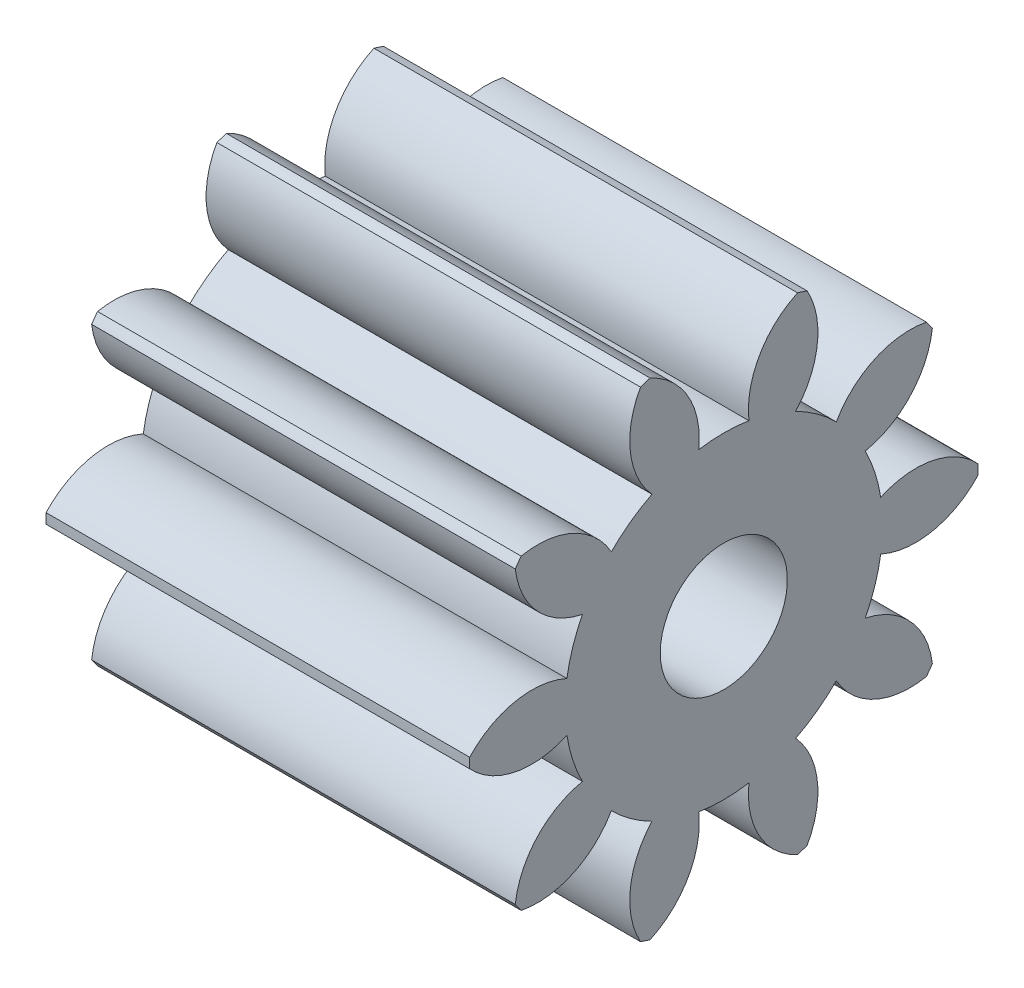
SolidWorks part; units mm, degrees
ref_plane "Plane1" through (0, 0, 0) normal (0, 0, 1) x (1, 0, 0)
ref_plane "Plane2" through (0, 0, 0) normal (0, 1, 0) x (1, 0, 0)
ref_plane "Plane3" through (0, 0, 0) normal (1, 0, 0) x (0, 0, -1)
other "Configuration Table"
sketch "HoldingSke" plane through (0, 0, 0) normal (0, 1, 0) x (1, 0, 0)
  line L0 (0, 0) -> (0.9848, -0.1736)
  line L1 (-15, 0) -> (100, 0) construction
  line L2 (0, 0) -> (-2.1039, 2.3779)
  line L3 (0, 0) -> (-11.863, 4.5341)
  line L4 (0, 0) -> (8.5048, 1.4996)
  line L5 (0, 0) -> (-46.8476, -17.4728)
  line L6 (0, 0) -> (-8.2896, -5.593)
  line L7 (-2.1039, 2.3779) -> (8.6586, 51.2059)
  line L8 (-76.2, 54.61) -> (-75.7, 54.61)
  line L9 (-71.009, 38.7566) -> (-53.1078, 45.2721)
  line L10 (-76.2, 71.12) -> (104.1128, 71.12)
  line L11 (0, 0) -> (-10, 0)
  line L12 (-76.2, 101.6) -> (-76.162, 101.6)
  line L13 (24.9733, 27.94) -> (52.9518, 28.4284)
  line L14 (24.9733, 27.94) -> (24.9743, 27.94)
  line L15 (24.9733, 27.94) -> (100.4006, 29.5858)
  line L16 (-63.627, -1) -> (-12.827, -1)
  circle A0 centre (0, 0) radius 1.5
  circle A1 centre (0, 0) radius 3.749
  circle A2 centre (0, 0) radius 37.5
  circle A3 centre (0, 0) radius 1.5
  dimension "MHD" = 7.498
  dimension "Hub_dia" = 75
  dimension "Bore" = 3
  dimension "MBD" = 3
  dimension "Num_teeth" = 10
  dimension "Pitch" = 1
  dimension "Overall_len" = 50
  dimension "Show_teeth" = 10
  dimension "Thickness" = 10
  dimension "OAL" = 50.0001
  dimension "T_dim" = 0.5
  dimension "Ap" = 20
  dimension "H" = 19.05
  dimension "Pitch_radius" = 180.3128
  dimension "Width" = 10
  dimension "Backlash" = 0.038
  dimension "Addendum_fac" = 1
  dimension "Dedendum_fac" = 1.25
  dimension "Clearance_fac" = 0.25
  dimension "Dedendum_add" = 0.001
  dimension "Module" = 1
sketch "BasProSke" plane through (0, 0, 0) normal (0, 1, 0) x (1, 0, 0)
  line L0 (-10, 0) -> (60, 0) construction
  line L1 (0, 0) -> (0, 6)
  line L2 (0, 0) -> (10, 0)
  line L3 (10, 0) -> (10, 6)
  line L4 (10, 6) -> (0, 6)
  dimension "Thickness" = 10
  dimension "Diameter" = 12
revolve "Base-Revolve" add sketch "BasProSke" angle 360 about L0
sketch "TooCutSke" plane through (0, 0, 0) normal (1, 0, 0) x (0, 0, -1)
  line L1 (0, 0) -> (0, 107) construction
  line L2 (0, 0) -> (-0.8485, 4.9275) construction
  line L3 (0, 0) -> (-3.0584, 9.4126) construction
  line L4 (-0.8485, 4.9275) -> (-1.5292, 4.7063) construction
  arc A0 (0.5928, 3.7018) -> (-0.5928, 3.7018) centre (0, 0) ccw
  arc A1 (1.7758, 5.7578) -> (-1.7758, 5.7578) centre (0, 0) ccw
  circle A2 centre (0, 0) radius 5 construction
  circle A3 centre (0, 0) radius 4.6985 construction
  arc A4 (-0.5928, 3.7018) -> (-1.7758, 5.7578) centre (-2.5801, 3.9267) ccw
  arc A5 (1.7758, 5.7578) -> (0.5928, 3.7018) centre (2.5801, 3.9267) ccw
  dimension "Root_dia" = 7.498
  dimension "Overcut_dia" = 12.0508
  dimension "Pitch_dia" = 10
  dimension "Base_dia" = 9.3969
  dimension "Flank_rad" = 2
  dimension "Half_ang" = 18
  dimension "Half_CT" = 0.7157
extrude "ToothCut" cut sketch "TooCutSke" along normal through all
fillet "Breaks" [suppressed] radius 0.02
fillet "RootFillets" [suppressed] radius 0.251
pattern_circular "TeethCuts" count 10 every 36 about axis through (-10, 0, 0) along (1, 0, 0) of "ToothCut", "RootFillets", "Breaks"
sketch "HubNeaOneSke" plane through (0, 0, 0) normal (-1, 0, 0) x (0, 0, 1)
  circle A0 centre (0, 0) radius 3.749
  dimension "Diameter" = 7.498
extrude "HubNearOne" [suppressed] add sketch "HubNeaOneSke" along normal blind 40.0001
sketch "HubNeaBotSke" plane through (0, 0, 0) normal (-1, 0, 0) x (0, 0, 1)
  circle A0 centre (0, 0) radius 3.749
  dimension "Diameter" = 7.498
extrude "HubNearBoth" [suppressed] add sketch "HubNeaBotSke" along normal blind 20
ref_plane "FarPln" through (10, 0, 0) normal (1, 0, 0) x (0, 0, -1)
sketch "HubFarSke" plane through (10, 0, 0) normal (1, 0, 0) x (0, 0, -1)
  circle A0 centre (0, 0) radius 3.749
  dimension "Diameter" = 7.498
extrude "HubFar" [suppressed] add sketch "HubFarSke" along normal blind 20
sketch "BorSke" plane through (0, 0, 0) normal (1, 0, 0) x (0, 0, -1)
  circle A0 centre (0, 0) radius 1.5
  dimension "Diameter" = 3
extrude "Bore" cut sketch "BorSke" along normal mid plane 100.0001
sketch "KeySke" plane through (0, 0, 0) normal (1, 0, 0) x (0, 0, -1)
  line L0 (-0.6, 0) -> (-0.6, 2)
  line L1 (-0.6, 2) -> (0.6, 2)
  line L2 (0.6, 2) -> (0.6, 0)
  line L3 (0, 0) -> (0, 34) construction
  line L4 (-0.6, 0) -> (0.6, 0)
  dimension "Offset" = 2
  dimension "Width" = 1.2
extrude "Keyway" [suppressed] cut sketch "KeySke" along normal mid plane 100.0001
pattern_circular "Keyway2" [suppressed] count 2 every 90 about axis through (-10, 0, 0) along (1, 0, 0)
equation "' \"Module@HoldingSke\" = 6.35"
equation "' \"Num_teeth@HoldingSke\" = 12"
equation "' \"Ap@HoldingSke\" =  20"
equation "' \"Ap@HoldingSke\" = 20"
equation "' \"Width@HoldingSke\" = 0.5 * 25.4"
equation "' \"Hub_dia@HoldingSke\"= 1 * 25.4"
equation "' \"Hub_dia@HoldingSke\" = 1 * 25.4"
equation "' \"Overall_len@HoldingSke\" = 1.0 * 25.4"
equation "' \"Bore@HoldingSke\" = 0.75 * 25.4"
equation "' \"T_dim@HoldingSke\" = 0.1 * 25.4"
equation "' \"Width@KeySke\" = 0.25 * 25.4"
equation "' \"Show_teeth@HoldingSke\" = 13"
equation "' \"Backlash@HoldingSke\" = 0.009 * 25.4"
equation "' \"Addendum_fac@HoldingSke\" = 1.0"
equation "' \"Dedendum_fac@HoldingSke\" = 1.25"
equation "' \"Dedendum_add@HoldingSke\" = 0.00005 * 25.4"
equation "' \"Clearance_fac@HoldingSke\" = 0.25"
equation "\"Pitch@HoldingSke\" = 1 / \"Module@HoldingSke\""
equation "\"Overcut_dia@TooCutSke\" = (\"Num_teeth@HoldingSke\" + 2 * \"Addendum_fac@HoldingSke\") / \"Pitch@HoldingSke\" + 0.002 * 25.4"
equation "\"Pitch_dia@TooCutSke\" = \"Num_teeth@HoldingSke\" / \"Pitch@HoldingSke\""
equation "\"Base_dia@TooCutSke\" = \"Num_teeth@HoldingSke\" / \"Pitch@HoldingSke\" * cos((\"Ap@HoldingSke\"  * 3.14159265 / 180))"
equation "\"Root_dia@TooCutSke\" = (\"Num_teeth@HoldingSke\" + 2) / \"Pitch@HoldingSke\" - 2 * (\"Addendum_fac@HoldingSke\" + \"Dedendum_fac@HoldingSke\") / \"Pitch@HoldingSke\" - \"Dedendum_add@HoldingSke\" * 2"
equation "\"Half_ang@TooCutSke\" = 180 / \"Num_teeth@HoldingSke\""
equation "\"Half_CT@TooCutSke\" = \"Num_teeth@HoldingSke\" / \"Pitch@HoldingSke\" * sin((3.14159265 / 2 / \"Num_teeth@HoldingSke\")) / 2 - 7 * \"Backlash@HoldingSke\" / 4"
equation "\"Flank_rad@TooCutSke\" = \"Num_teeth@HoldingSke\" / \"Pitch@HoldingSke\" / 5"
equation "\"Radius@RootFillets\" = \"Clearance_fac@HoldingSke\" / \"Pitch@HoldingSke\" + \"Dedendum_add@HoldingSke\""
equation "\"Break_rad@Breaks\" = 0.02 / \"Pitch@HoldingSke\""
equation "\"Thickness@HoldingSke\" = \"Width@HoldingSke\""
equation "\"OAL@HoldingSke\" = \"Thickness@HoldingSke\""
equation "\"MHD@HoldingSke\" = (\"Num_teeth@HoldingSke\" + 2) / \"Pitch@HoldingSke\" - 2 * (\"Addendum_fac@HoldingSke\" + \"Dedendum_fac@HoldingSke\")  / \"Pitch@HoldingSke\" - \"Dedendum_add@HoldingSke\" * 2"
equation "\"MBD@HoldingSke\" = (\"Num_teeth@HoldingSke\" + 2) / \"Pitch@HoldingSke\" - 2 * (\"Addendum_fac@HoldingSke\" + \"Dedendum_fac@HoldingSke\")  / \"Pitch@HoldingSke\" - \"Dedendum_add@HoldingSke\" * 2 - 0.002 * 25.4"
equation "\"MHD@HoldingSke\" = ((sgn( \"MHD@HoldingSke\" - \"Hub_dia@HoldingSke\" )-1)*( \"MHD@HoldingSke\" - \"Hub_dia@HoldingSke\" ))/-2+ \"Hub_dia@HoldingSke\""
equation "\"MBD@HoldingSke\" = ((sgn( \"MBD@HoldingSke\" - \"Bore@HoldingSke\" )-1)*( \"MBD@HoldingSke\" - \"Bore@HoldingSke\" ))/-2+ \"Bore@HoldingSke\""
equation "\"OAL@HoldingSke\" = ((sgn( \"OAL@HoldingSke\" - \"Overall_len@HoldingSke\" )+1)*( \"OAL@HoldingSke\" - \"Overall_len@HoldingSke\" ))/2 + \"Overall_len@HoldingSke\" + 0.000002 * 25.4"
equation "\"Num_teeth@TeethCuts\" = int( \"Show_teeth@HoldingSke\" ) + 1"
equation "\"Num_teeth@TeethCuts\" = ((sgn( \"Num_teeth@TeethCuts\" - \"Num_teeth@HoldingSke\" )-1)*( \"Num_teeth@TeethCuts\" - \"Num_teeth@HoldingSke\" ))/-2+ \"Num_teeth@HoldingSke\""
equation "\"Num_teeth@TeethCuts\" = ((sgn( \"Num_teeth@TeethCuts\" - 2.0)+1)*( \"Num_teeth@TeethCuts\" - 2.0))/2 +2.0"
equation "\"Angle@TeethCuts\" = 360.0 / \"Num_teeth@HoldingSke\""
equation "\"Diameter@BasProSke\" = (\"Num_teeth@HoldingSke\" + 2 * \"Addendum_fac@HoldingSke\") / \"Pitch@HoldingSke\""
equation "\"Thickness@BasProSke\"  = \"Thickness@HoldingSke\""
equation "' \"Fillet_rad@BasProSke\" =  \"Thickness@HoldingSke\" * 0.05"
equation "' \"Fillet_rad@BasProSke\" = \"Thickness@HoldingSke\" * 0.05"
equation "\"MHD@HoldingSke\" = ((sgn( \"MHD@HoldingSke\" - \"Root_dia@TooCutSke\" )-1)*( \"MHD@HoldingSke\" - \"Root_dia@TooCutSke\" ))/-2+ \"Root_dia@TooCutSke\""
equation "\"Diameter@HubNeaOneSke\" = \"MHD@HoldingSke\""
equation "\"Length@HubNearOne\" = \"OAL@HoldingSke\" - \"Thickness@BasProSke\""
equation "\"Diameter@HubNeaBotSke\" = \"MHD@HoldingSke\""
equation "\"Length@HubNearBoth\" = ( \"OAL@HoldingSke\" - \"Thickness@BasProSke\" ) / 2.0"
equation "\"Thickness@FarPln\" = \"Thickness@BasProSke\""
equation "\"Diameter@HubFarSke\" = \"MHD@HoldingSke\""
equation "\"Length@HubFar\" = ( \"OAL@HoldingSke\" - \"Thickness@BasProSke\" ) / 2.0"
equation "\"Diameter@BorSke\" = \"MBD@HoldingSke\""
equation "\"D1@Bore\" = \"OAL@HoldingSke\" * 2.0"
equation "\"D1@Keyway\" = \"OAL@HoldingSke\" * 2.0"
equation "\"Offset@KeySke\" = \"T_dim@HoldingSke\" + \"MBD@HoldingSke\" / 2.0"
